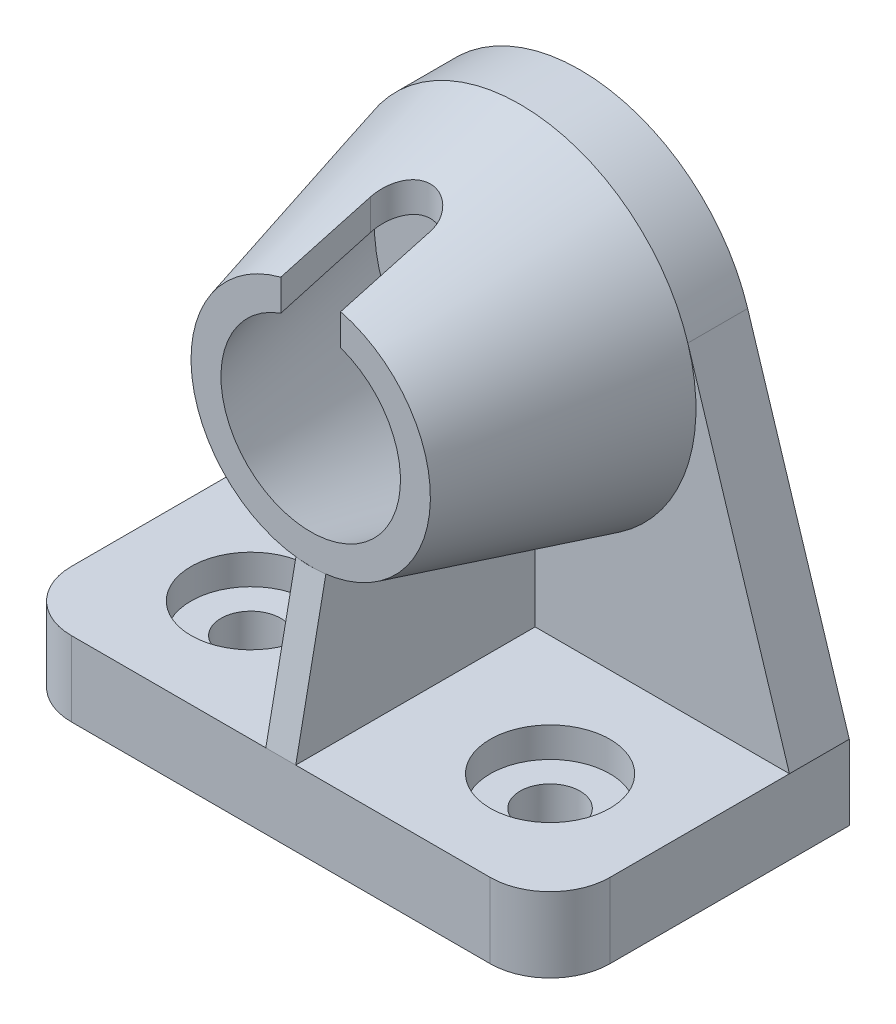
SolidWorks part; units mm, degrees
ref_plane "Front Plane" through (0, 0, 0) normal (0, 0, 1) x (1, 0, 0)
ref_plane "Top Plane" through (0, 0, 0) normal (0, 1, 0) x (1, 0, 0)
ref_plane "Right Plane" through (0, 0, 0) normal (1, 0, 0) x (0, 0, -1)
sketch "Sketch1" plane through (0, 0, 0) normal (1, 0, 0) x (0, 0, -1)
  line L0 (0, 30) -> (0, 40)
  line L1 (0, 40) -> (70, 58.7564)
  line L2 (70, 58.7564) -> (70, 48.7564)
  line L3 (70, 48.7564) -> (0, 30)
  line L4 (0, 0) -> (63.1524, 0) construction
  dimension "D1" = 70
  dimension "D2" = 10
  dimension "D3" = 30
  dimension "D4" = 15
revolve "Revolve1" add sketch "Sketch1" angle 360 about L4
sketch "Sketch2" plane through (0, 0, -70) normal (0, 0, -1) x (-1, 0, 0)
  line L0 (0, 0) -> (0, -90) construction
  line L1 (90, -90) -> (-90, -90)
  line L2 (-90, -90) -> (-56.0347, 17.6756)
  line L3 (90, -90) -> (56.0347, 17.6756)
  arc A0 (56.0347, 17.6756) -> (-56.0347, 17.6756) centre (0, 0) ccw
  circle A1 centre (0, 0) radius 58.7564 construction
  circle A2 centre (0, 0) radius 20
  dimension "D3" = 40
  dimension "D1" = 90
  dimension "D2" = 180
extrude "Boss-Extrude1" add sketch "Sketch2" along normal blind 20
sketch "Sketch3" plane through (0, -90, 0) normal (0, -1, 0) x (1, 0, 0)
  line L0 (90, -90) -> (90, -70) construction
  line L1 (-90, -90) -> (90, -90)
  line L2 (-90, -90) -> (-90, -10)
  line L3 (-70, 10) -> (70, 10)
  line L4 (90, -90) -> (90, -10)
  arc A0 (70, 10) -> (90, -10) centre (70, -10) cw
  arc A1 (-90, -10) -> (-70, 10) centre (-70, -10) cw
  dimension "D1" = 20
  dimension "D2" = 100
extrude "Boss-Extrude2" add sketch "Sketch3" along normal blind 25
sketch "Sketch4" plane through (0, 0, 0) normal (0, 1, 0) x (1, 0, 0)
  line L0 (0, -30) -> (0, 30) construction
  line L1 (-10, -30) -> (-10, 30)
  line L2 (10, -30) -> (10, 30)
  arc A0 (-10, -30) -> (10, -30) centre (0, -30) ccw
  arc A1 (10, 30) -> (-10, 30) centre (0, 30) ccw
  point P2 (0, 0)
  dimension "D1" = 10
  dimension "D2" = 60
extrude "Cut-Extrude1" cut sketch "Sketch4" along normal through all
sketch "Sketch5" plane through (0, 0, 0) normal (1, 0, 0) x (0, 0, -1)
  line L0 (-10, -90) -> (0, -40)
  line L1 (0, 38.7298) -> (0, -40) construction
rib "Rib1" sketch "Sketch5" sketch "Sketch5" thickness 10 extrusion direction parallel to sketch draft on no parameters "D1"=10
hole_wizard "Hole1" positions "Sketch6" profile "Sketch7" legacy
sketch "Sketch6" plane through (0, -90, 0) normal (0, 1, 0) x (1, 0, 0)
  line L0 (70, -10) -> (5, -10) construction
  point P0 (50, 30)
  dimension "D1" = 50
  dimension "D2" = 40
sketch "Sketch7" plane through (50, -90, -30) normal (1, 0, 0) x (0, 0, 1)
  line L0 (0, 0) -> (0, 25)
  line L1 (0, 25) -> (10, 25)
  line L2 (10, 25) -> (10, 10)
  line L3 (10, 10) -> (20, 10)
  line L4 (20, 10) -> (20, 0)
  line L5 (20, 0) -> (0, 0)
  line L6 (0, 110) -> (0, -10) construction
  dimension "Diameter" = 20
  dimension "Depth" = 25
  dimension "C-Bore Diameter" = 40
  dimension "C-Bore Depth" = 10
mirror "Mirror1" about plane through (0, 0, 0) normal (1, 0, 0) of "Hole1"
